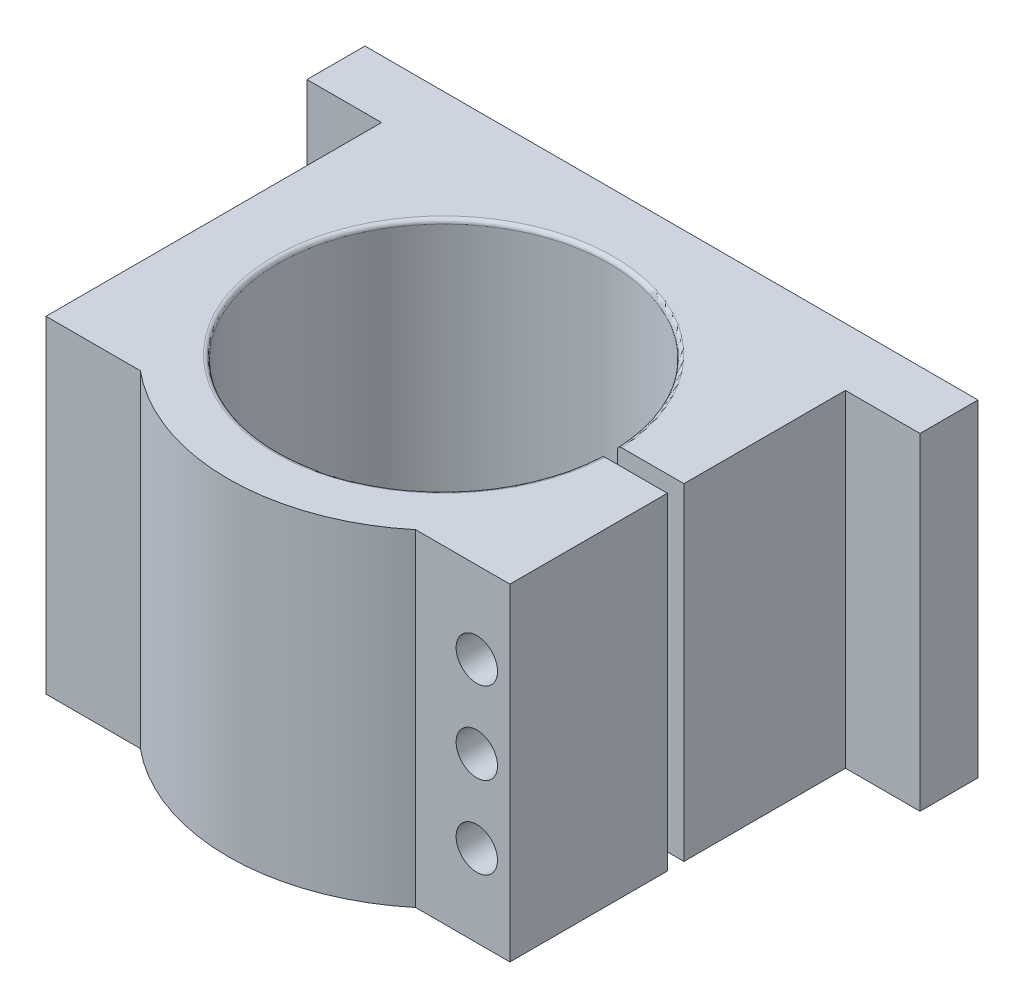
SolidWorks part; units mm, degrees
material "1060 Alloy"
ref_plane "Front Plane" through (0, 0, 0) normal (0, 0, 1) x (1, 0, 0)
ref_plane "Top Plane" through (0, 0, 0) normal (0, 1, 0) x (1, 0, 0)
ref_plane "Right Plane" through (0, 0, 0) normal (1, 0, 0) x (0, 0, -1)
sketch "Sketch1" plane through (0, 0, 0) normal (0, 0, 1) x (1, 0, 0)
  line L1 (-74, -39.5) -> (74, -39.5)
  line L2 (-74, -39.5) -> (-74, 39.5)
  line L3 (-74, 39.5) -> (74, 39.5)
  line L4 (74, -39.5) -> (74, 39.5)
  line L5 (-74, -39.5) -> (74, 39.5) construction
  line L6 (-74, 39.5) -> (74, -39.5) construction
  point P0 (0, 0)
extrude "Boss-Extrude1" add sketch "Sketch1" along normal blind 14
sketch "Sketch2" plane through (0, 0, 14) normal (0, 0, 1) x (1, 0, 0)
  line L1 (56, -39.5) -> (-56, -39.5)
  line L2 (56, -39.5) -> (56, 39.5)
  line L3 (56, 39.5) -> (-56, 39.5)
  line L4 (-56, -39.5) -> (-56, 39.5)
  line L5 (56, -39.5) -> (-56, 39.5) construction
  line L6 (56, 39.5) -> (-56, -39.5) construction
  point P0 (0, 0)
extrude "Boss-Extrude2" add sketch "Sketch2" along normal blind 93
sketch "Sketch3" plane through (0, 39.5, 0) normal (0, 1, 0) x (1, 0, 0)
  line L0 (0, -95) -> (0, -107)
  line L1 (56, -107) -> (-56, -107) construction
  circle A0 centre (0, -55) radius 40
extrude "Cut-Extrude1" cut sketch "Sketch3" against normal blind 80 contours A0
sketch "Sketch6" plane through (0, 39.5, 0) normal (0, 1, 0) x (1, 0, 0)
  line L0 (-33.2265, -95) -> (-56, -95)
  line L1 (-56, -107) -> (-56, -14) construction
  line L2 (33.2265, -95) -> (56, -95)
  line L3 (56, -107) -> (56, -14) construction
  line L6 (-56, -95) -> (-56, -107)
  line L7 (-56, -107) -> (56, -107)
  line L8 (56, -107) -> (56, -95)
  arc A0 (0, -107) -> (-33.2265, -95) centre (0, -55) cw
  arc A1 (0, -107) -> (33.2265, -95) centre (0, -55) ccw
  line M5 (-56, -14) -> (-56, -107)
  line M6 (-56, -107) -> (56, -107)
  line M7 (56, -107) -> (56, -14)
extrude "Cut-Extrude2" cut sketch "Sketch6" against normal blind 80 contours A0 L0 M6 M5 | A1 L7 L2 M7
sketch "Sketch8" plane through (0, 39.5, 0) normal (0, 1, 0) x (1, 0, 0)
  line L1 (56, -55) -> (56, -57)
  line L2 (56, -95) -> (56, -14) construction
  line L3 (56, -55) -> (56, -53)
  line L4 (56, -53) -> (38.221, -53)
  line L5 (38.221, -53) -> (38.221, -57)
  line L6 (38.221, -57) -> (56, -57)
extrude "Cut-Extrude4" cut sketch "Sketch8" against normal blind 80
sketch "Sketch9" plane through (0, 0, 95) normal (0, 0, 1) x (1, 0, 0)
  circle A0 centre (48, 19.75) radius 3
  circle A1 centre (48, 0) radius 3
  circle A2 centre (48, -19.75) radius 3
extrude "Cut-Extrude5" cut sketch "Sketch9" against normal blind 60
sketch "Sketch10" plane through (0, 0, 95) normal (0, 0, 1) x (1, 0, 0)
  circle A0 centre (48, 19.75) radius 5
  circle A1 centre (48, 0) radius 5
  circle A2 centre (48, -19.75) radius 5
extrude "Cut-Extrude6" cut sketch "Sketch10" against normal blind 10
fillet "Fillet1" radius 1 2 edges at (-40, 39.5, 55) (-40, -39.5, 55)
